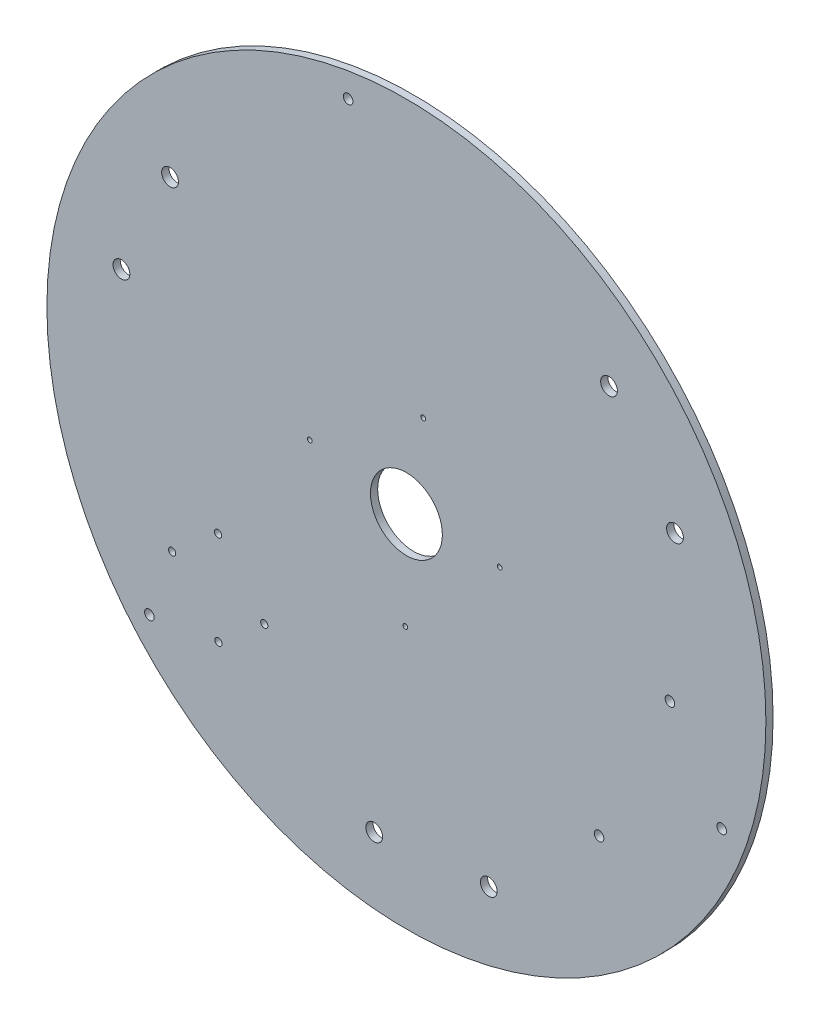
SolidWorks part; units mm, degrees
ref_plane "Front Plane" through (0, 0, 0) normal (0, 0, 1) x (1, 0, 0)
ref_plane "Top Plane" through (0, 0, 0) normal (0, 1, 0) x (1, 0, 0)
ref_plane "Right Plane" through (0, 0, 0) normal (1, 0, 0) x (0, 0, -1)
sketch "Sketch1" plane through (0, 0, 0) normal (0, 0, 1) x (1, 0, 0)
  circle A0 centre (0, 0) radius 150
  dimension "D1" = 300
extrude "Boss-Extrude1" add sketch "Sketch1" along normal blind 3
sketch "Sketch2" plane through (0, 0, 0) normal (0, 0, -1) x (-1, 0, 0)
  line L0 (0, 0) -> (0, 199.4542) construction
  line L1 (0, 0) -> (-183.0223, 128.1536) construction
  line L6 (-84.5324, 88.4888) -> (-112.0641, 49.1695) construction
  circle A0 centre (-84.5324, 88.4888) radius 3.5
  circle A1 centre (-112.0641, 49.1695) radius 3.5
  dimension "D6" = 7
  dimension "D1" = 55
  dimension "D2" = 24
  dimension "D3" = 120
extrude "Cut-Extrude1" cut sketch "Sketch2" against normal up to surface (3 mm away) up to face at (150, 0, 3)
pattern_circular "CirPattern1" count 3 over 360 about axis through (0, 0, 0) along (0, 0, 1) of "Cut-Extrude1"
sketch "Sketch3" plane through (0, 0, 0) normal (0, 0, -1) x (-1, 0, 0)
  line L0 (0, 0) -> (-135.9462, -63.3927) construction
  line L1 (-80.3707, -76.0957) -> (-109.954, -12.6541) construction
  line L2 (-84.5324, 88.4888) -> (-112.0641, 49.1695) construction
  line L4 (0, 0) -> (-98.2982, 68.8292) construction
  circle A0 centre (0, 0) radius 150 construction
  circle A1 centre (-109.954, -12.6541) radius 2
  circle A2 centre (-80.3707, -76.0957) radius 2
  dimension "D1" = 4
  dimension "D2" = 4
  dimension "D5" = 60
  dimension "D3" = 35
  dimension "D4" = 45
extrude "Cut-Extrude2" cut sketch "Sketch3" against normal up to surface (3 mm away) up to face at (37.8674, -117.4516, 3)
sketch "Sketch4" plane through (0, 0, 0) normal (0, 0, -1) x (-1, 0, 0)
  circle A0 centre (0, 0) radius 15
  dimension "D1" = 30
extrude "Cut-Extrude3" cut sketch "Sketch4" against normal up to surface (3 mm away) up to face at (111.954, -12.6541, 3)
sketch "Sketch5" plane through (0, 0, 0) normal (0, 0, -1) x (-1, 0, 0)
  line L0 (-109.954, -12.6541) -> (-80.3707, -76.0957) construction
  line L1 (0, 0) -> (64.1001, -53.7864) construction
  line L2 (0, 0) -> (-43.666, -52.0391) construction
  line L3 (0, 0) -> (96.4181, 114.9067) construction
  line L4 (-7.0402, 38.2815) -> (-38.9225, 0.2857) construction
  line L5 (0, 0) -> (-38.2702, 32.1126) construction
  line L6 (-34.3674, -117.4516) -> (13.45, -121.6351) construction
  line L7 (0, 0) -> (-10.4587, -119.5434) construction
  circle A0 centre (0.4515, -40.8465) radius 1
  circle A1 centre (-38.9225, 0.2857) radius 1
  circle A2 centre (40.3043, 6.6483) radius 1
  circle A3 centre (-7.0402, 38.2815) radius 1
  circle A4 centre (0, 0) radius 150 construction
  dimension "D1" = 2
  dimension "D2" = 2
  dimension "D4" = 2
  dimension "D5" = 2
  dimension "D3" = 31
  dimension "D6" = 24.8
  dimension "D7" = 56.94
  dimension "D8" = 30
  dimension "D9" = 55
extrude "Cut-Extrude4" cut sketch "Sketch5" against normal up to surface (3 mm away) up to face at (15, 0, 3)
sketch "Sketch6" plane through (0, 0, 0) normal (0, 0, -1) x (-1, 0, 0)
  line L0 (59.3022, -69.3416) -> (78.5858, -46.3602) construction
  line L2 (-34.3674, -117.4516) -> (13.45, -121.6351) construction
  line L4 (0, 0) -> (-10.4587, -119.5434) construction
  line L5 (0, 0) -> (146.4579, -122.8927) construction
  circle A4 centre (59.3022, -69.3416) radius 1.5
  circle A5 centre (78.4533, -85.4112) radius 1.5
  circle A6 centre (97.7369, -62.4299) radius 1.5
  circle A7 centre (78.5858, -46.3602) radius 1.5
  dimension "D2" = 3
  dimension "D3" = 3
  dimension "D4" = 3
  dimension "D5" = 3
  dimension "D6" = 15
  dimension "D7" = 15
  dimension "D8" = 25
  dimension "D9" = 90
  dimension "D10" = 55
extrude "Cut-Extrude5" cut sketch "Sketch6" against normal up to surface (3 mm away) up to face at (0.5485, -40.8465, 3)
sketch "Sketch7" plane through (0, 0, 0) normal (0, 0, -1) x (-1, 0, 0)
  line L0 (78.5858, -46.3602) -> (59.3022, -69.3416) construction
  line L1 (0, 0) -> (114.9067, -96.4181) construction
  circle A0 centre (0, 0) radius 150 construction
  circle A1 centre (107.2462, -89.9903) radius 2
  dimension "D1" = 4
  dimension "D2" = 10
extrude "Cut-Extrude6" cut sketch "Sketch7" against normal up to surface (3 mm away) up to face at (-57.8022, -69.3416, 3)
pattern_circular "CirPattern2" count 3 over 360 about axis through (0, 0, 0) along (0, 0, 1) of "Cut-Extrude6"
